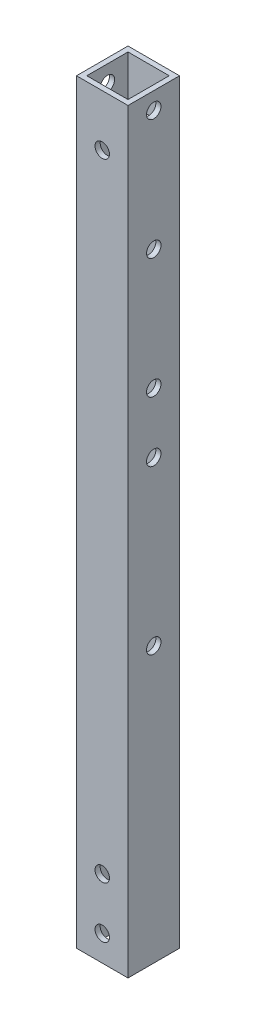
SolidWorks part; units mm, degrees
material "5052-H34"
ref_plane "正面" through (0, 0, 0) normal (0, 0, 1) x (1, 0, 0)
ref_plane "平面" through (0, 0, 0) normal (0, 1, 0) x (1, 0, 0)
ref_plane "右側面" through (0, 0, 0) normal (1, 0, 0) x (0, 0, -1)
sketch "ｽｹｯﾁ1" plane through (0, 0, 0) normal (0, 1, 0) x (1, 0, 0)
  line L1 (-7.5, 7.5) -> (7.5, 7.5)
  line L2 (-7.5, 7.5) -> (-7.5, -7.5)
  line L3 (-7.5, -7.5) -> (7.5, -7.5)
  line L4 (7.5, 7.5) -> (7.5, -7.5)
  line L5 (-7.5, 7.5) -> (7.5, -7.5) construction
  line L6 (-7.5, -7.5) -> (7.5, 7.5) construction
  point P0 (0, 0)
  dimension "D1" = 15
extrude "押し出し-薄板1" add sketch "ｽｹｯﾁ1" along normal blind 220 thin
sketch "ｽｹｯﾁ2" plane through (7.5, 0, 0) normal (1, 0, 0) x (0, 0, -1)
  line L0 (0, 220) -> (0, 215) construction
  line L1 (-7.5, 220) -> (7.5, 220) construction
  circle A0 centre (0, 215) radius 2.1
  dimension "D1" = 4.2
  dimension "D2" = 5
extrude "ｶｯﾄ - 押し出し1" cut sketch "ｽｹｯﾁ2" against normal through all
sketch "ｽｹｯﾁ3" plane through (7.5, 0, 0) normal (1, 0, 0) x (0, 0, -1)
  line L0 (0, 220) -> (0, 145) construction
  line L1 (-7.5, 220) -> (7.5, 220) construction
  circle A0 centre (0, 145) radius 2.1
  circle A1 centre (0, 180) radius 2.1
  dimension "D1" = 4.2
  dimension "D2" = 35
  dimension "D3" = 40
extrude "ｶｯﾄ - 押し出し2" cut sketch "ｽｹｯﾁ3" against normal through all
sketch "ｽｹｯﾁ4" plane through (0, 0, 7.5) normal (0, 0, 1) x (1, 0, 0)
  line L0 (0, 220) -> (0, 205) construction
  line L1 (-7.5, 220) -> (7.5, 220) construction
  circle A0 centre (0, 205) radius 2.1
  dimension "D1" = 4.2
  dimension "D2" = 15
extrude "ｶｯﾄ - 押し出し3" cut sketch "ｽｹｯﾁ4" against normal through all
sketch "ｽｹｯﾁ5" plane through (0, 0, 7.5) normal (0, 0, 1) x (1, 0, 0)
  line L0 (0, 0) -> (0, 22.5) construction
  circle A0 centre (0, 22.5) radius 2.1
  circle A1 centre (0, 7.5) radius 2.1
  dimension "D1" = 4.2
  dimension "D2" = 7.5
  dimension "D3" = 15
extrude "ｶｯﾄ - 押し出し4" cut sketch "ｽｹｯﾁ5" against normal through all
sketch "ｽｹｯﾁ6" plane through (7.5, 0, 0) normal (1, 0, 0) x (0, 0, -1)
  line L0 (0, 220) -> (0, 80) construction
  line L1 (-7.5, 220) -> (7.5, 220) construction
  circle A0 centre (0, 80) radius 2.1
  circle A1 centre (0, 127.5) radius 2.1
  dimension "D1" = 4.2
  dimension "D2" = 92.5
  dimension "D3" = 140
extrude "ｶｯﾄ - 押し出し5" cut sketch "ｽｹｯﾁ6" against normal through all
